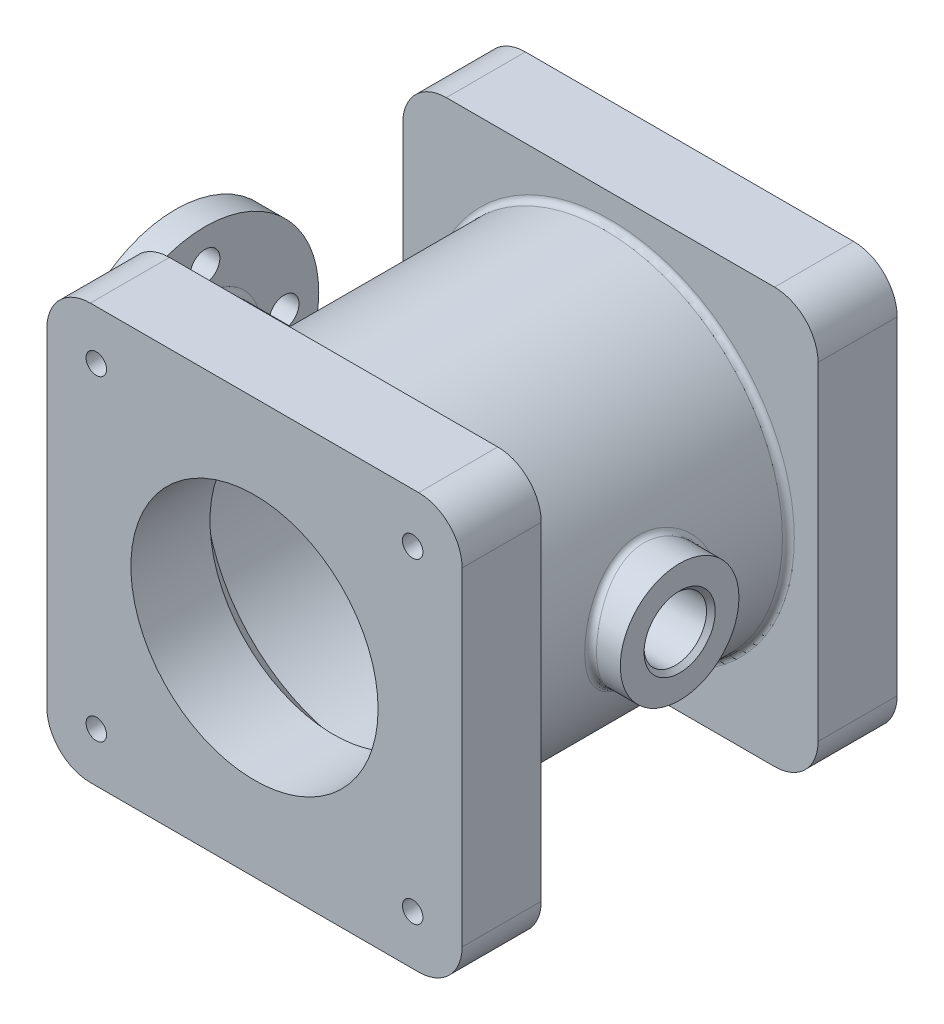
SolidWorks part; units mm, degrees
material "Сталь 12Х17 ГОСТ 5632-72"
ref_plane "Спереди" through (0, 0, 0) normal (0, 0, 1) x (1, 0, 0)
ref_plane "Сверху" through (0, 0, 0) normal (0, 1, 0) x (1, 0, 0)
ref_plane "Справа" through (0, 0, 0) normal (1, 0, 0) x (0, 0, -1)
sketch "Эскиз1" plane through (0, 0, 0) normal (0, 0, 1) x (1, 0, 0)
  line L4 (-83, -105) -> (83, -105)
  line L5 (105, -83) -> (105, 83)
  line L6 (83, 105) -> (-83, 105)
  line L7 (-105, 83) -> (-105, -83)
  line L8 (-83, -105) -> (83, -105)
  line L9 (105, -83) -> (105, 83)
  line L10 (83, 105) -> (-83, 105)
  line L11 (-105, 83) -> (-105, -83)
  arc A4 (83, -105) -> (105, -83) centre (83, -83) ccw
  arc A5 (105, 83) -> (83, 105) centre (83, 83) ccw
  arc A6 (-83, 105) -> (-105, 83) centre (-83, 83) ccw
  arc A7 (-105, -83) -> (-83, -105) centre (-83, -83) ccw
  arc A8 (83, -105) -> (105, -83) centre (83, -83) ccw
  arc A9 (105, 83) -> (83, 105) centre (83, 83) ccw
  arc A10 (-83, 105) -> (-105, 83) centre (-83, 83) ccw
  arc A11 (-105, -83) -> (-83, -105) centre (-83, -83) ccw
  dimension "D1" = 0
extrude "Бобышка-Вытянуть1" add sketch "Эскиз1" along normal blind 40
sketch "Эскиз2" plane through (0, 0, 40) normal (0, 0, 1) x (1, 0, 0)
  circle A0 centre (0, 0) radius 90
  circle A1 centre (0, 0) radius 1
  circle A2 centre (0, 0) radius 80
  dimension "D1" = 180
  dimension "D2" = 160
extrude "Бобышка-Вытянуть2" add sketch "Эскиз2" along normal blind 70 contours A0 A2
chamfer "Фаска1" distance 15 angle 45 1 edges at (80, 0, 40)
sketch "Эскиз3" plane through (0, 0, 40) normal (0, 0, 1) x (1, 0, 0)
  circle A0 centre (0, 0) radius 30
  dimension "D1" = 60
extrude "Вырез-Вытянуть1" cut sketch "Эскиз3" against normal through all
sketch "Эскиз4" plane through (0, 0, 0) normal (0, 0, -1) x (-1, 0, 0)
  circle A0 centre (-80, 80) radius 5.172
  circle A1 centre (80, 80) radius 5.172
  circle A2 centre (80, -80) radius 5.172
  circle A3 centre (-80, -80) radius 5.172
  dimension "D1" = 10.344
extrude "Вырез-Вытянуть2" cut sketch "Эскиз4" against normal blind 25
cosmetic thread "Условное изображение резьбы2" parameters "D2"=12
cosmetic thread "Условное изображение резьбы3" parameters "D2"=12
cosmetic thread "Условное изображение резьбы4" parameters "D2"=12
cosmetic thread "Условное изображение резьбы5" parameters "D2"=12
sketch "Эскиз5" plane through (0, 0, 0) normal (0, 0, -1) x (-1, 0, 0)
  circle A0 centre (0, 0) radius 62.5
  dimension "D1" = 125
extrude "Вырез-Вытянуть3" cut sketch "Эскиз5" against normal blind 5
ref_plane "Плоскость1" through (83, 105, -20) normal (-1, 0, 0) x (0, 0, 1)
mirror "Зеркальное отражение1" about plane through (0, 0, 110) normal (0, 0, 1) of bodies 109
sketch "Эскиз6" plane through (0, 0, 215) normal (0, 0, 1) x (1, 0, 0)
  circle A1 centre (0, 0) radius 62.5
  circle A2 centre (0, 0) radius 62.5
  dimension "D1" = 0
extrude "Бобышка-Вытянуть3" add sketch "Эскиз6" along normal up to surface (5 mm away) up to face at (-62.5, 0, 220)
sketch "Эскиз7" plane through (0, 0, 220) normal (0, 0, 1) x (1, 0, 0)
  circle A0 centre (0, 0) radius 62.5
  dimension "D1" = 125
extrude "Вырез-Вытянуть4" cut sketch "Эскиз7" against normal up to next
sketch "Эскиз8" plane through (0, 0, 0) normal (1, 0, 0) x (0, 0, -1)
  line L0 (-220, 0) -> (0, 0) construction
  line L1 (-220, -83) -> (-220, 83) construction
  circle A0 centre (-110, 0) radius 57.5
  dimension "D1" = 115
extrude "Бобышка-Вытянуть4" add sketch "Эскиз8" along normal blind 15 from offset 150 separate body offset against normal yes
sketch "Эскиз9" plane through (-135, 0, 0) normal (1, 0, 0) x (0, 0, -1)
  circle A0 centre (-110, 0) radius 25
  dimension "D1" = 50
extrude "Бобышка-Вытянуть5" add sketch "Эскиз9" along normal up to body separate body
sketch "Эскиз10" plane through (-150, 0, 0) normal (-1, 0, 0) x (0, 0, 1)
  circle A0 centre (110, 0) radius 12.5
  dimension "D1" = 25
extrude "Вырез-Вытянуть5" cut sketch "Эскиз10" against normal up to surface (70 mm away)
sketch "Эскиз11" plane through (-150, 0, 0) normal (-1, 0, 0) x (0, 0, 1)
  line L0 (110, 57.5) -> (110, -57.5) construction
  line L1 (52.5, 0) -> (167.5, 0) construction
  circle A0 centre (110, 0) radius 57.5 construction
  circle A1 centre (110, 40) radius 7.5
  point P9 (110, 0)
  dimension "D1" = 15
  dimension "D2" = 80
extrude "Вырез-Вытянуть6" cut sketch "Эскиз11" against normal up to next
pattern_circular "Круговой массив1" count 4 over 360 about axis through (0, 0, 110) along (1, 0, 0) of "Вырез-Вытянуть6"
fillet "Скругление1" radius 4 1 edges at (-79.9543, -2.7044, 97.7961)
sketch "Эскиз12" plane through (105, 0, 0) normal (1, 0, 0) x (0, 0, -1)
  line L0 (-220, 0) -> (0, 0) construction
  line L1 (-220, -83) -> (-220, 83) construction
  circle A0 centre (-110, 0) radius 30
  dimension "D1" = 60
extrude "Бобышка-Вытянуть6" add sketch "Эскиз12" against normal up to body separate body contours A0
sketch "Эскиз13" plane through (105, 0, 0) normal (1, 0, 0) x (0, 0, -1)
  circle A0 centre (-110, 0) radius 15.805
  dimension "D1" = 31.61
extrude "Вырез-Вытянуть7" cut sketch "Эскиз13" against normal up to surface (25 mm away)
cosmetic thread "Условное изображение резьбы6" parameters "D2"=36
chamfer "Фаска2" distance 2.195 angle 45 1 edges at (105, 0, 94.195)
fillet "Скругление2" radius 3 5 edges at (-89.8775, -4.6937, 85.4446) (90, 0, 180) (90, 0, 40) (89.8555, -5.0981, 139.5636) (-135, 0, 85)
